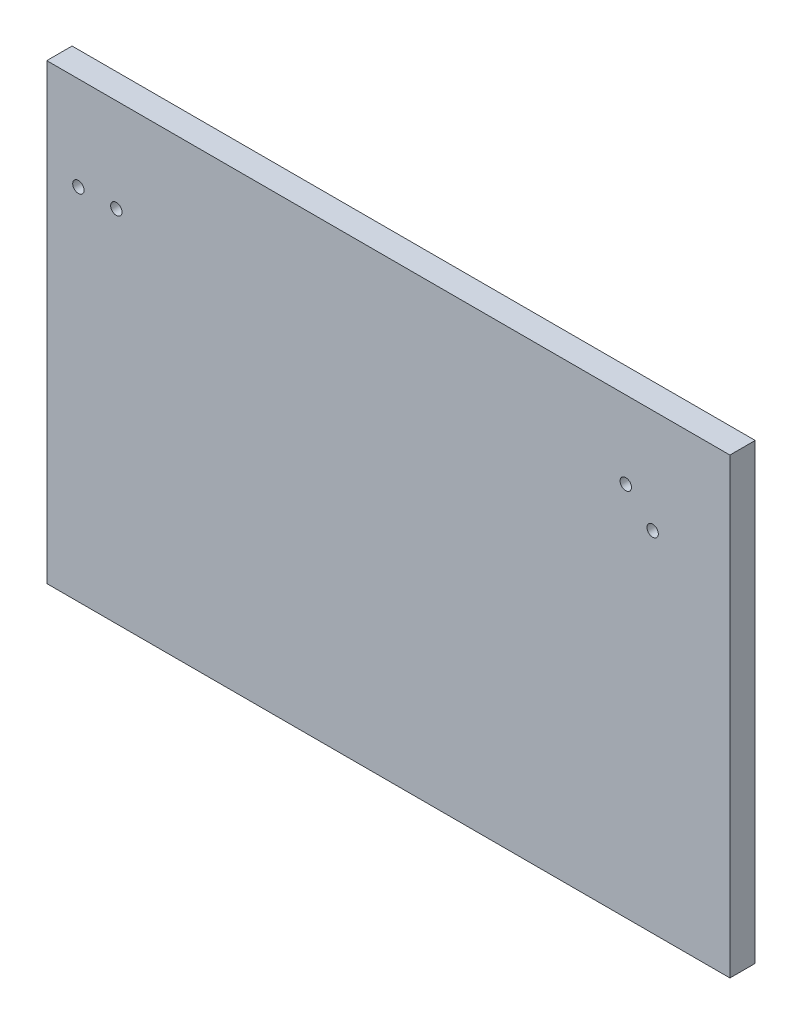
SolidWorks part; units mm, degrees
material "Multistrato di pioppo"
ref_plane "Piano frontale" through (0, 0, 0) normal (0, 0, 1) x (1, 0, 0)
ref_plane "Piano superiore" through (0, 0, 0) normal (0, 1, 0) x (1, 0, 0)
ref_plane "Piano destro" through (0, 0, 0) normal (1, 0, 0) x (0, 0, -1)
sketch "Schizzo1" plane through (0, 0, 0) normal (0, 0, 1) x (1, 0, 0)
  line L1 (0, 0) -> (-270, 0)
  line L2 (0, 0) -> (0, 179)
  line L3 (0, 179) -> (-270, 179)
  line L4 (-270, 0) -> (-270, 179)
  dimension "D1" = 270
  dimension "D2" = 179
extrude "Estrusione-Estrusione1" add sketch "Schizzo1" along normal blind 10
sketch "Schizzo2" plane through (0, 0, 0) normal (0, 0, -1) x (-1, 0, 0)
  circle A2 centre (41.1612, 148.4454) radius 2.25
  circle A3 centre (30.5546, 137.8388) radius 2.25
  circle A4 centre (242.5, 142) radius 2.25
  circle A5 centre (257.5, 142) radius 2.25
  dimension "D1" = 4.5
extrude "Taglio-Estrusione1" cut sketch "Schizzo2" against normal blind 10
